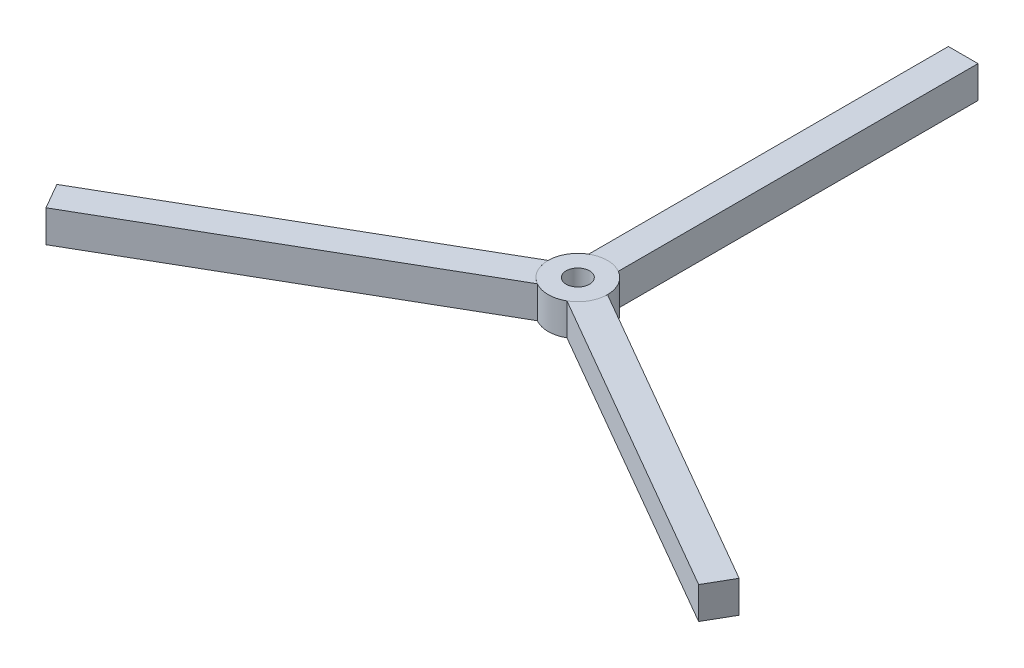
SolidWorks part; units mm, degrees
ref_plane "Front Plane" through (0, 0, 0) normal (0, 0, 1) x (1, 0, 0)
ref_plane "Top Plane" through (0, 0, 0) normal (0, 1, 0) x (1, 0, 0)
ref_plane "Right Plane" through (0, 0, 0) normal (1, 0, 0) x (0, 0, -1)
sketch "Sketch1" plane through (0, 0, 0) normal (0, 1, 0) x (1, 0, 0)
  circle A0 centre (0, 0) radius 6.35
  circle A1 centre (0, 0) radius 2.5
  dimension "D1" = 12.7
  dimension "D2" = 5
extrude "Boss-Extrude1" add sketch "Sketch1" along normal blind 6.858
ref_plane "Plane1" through (0, 0, -6.35) normal (0, 0, -1) x (-1, 0, 0)
sketch "Sketch3" plane through (0, 0, -6.35) normal (0, 0, -1) x (-1, 0, 0)
  line L0 (6.35, 6.858) -> (-6.35, 6.858) construction
  line L1 (-3.175, 6.858) -> (3.175, 6.858)
  line L2 (-3.175, 6.858) -> (-3.175, 0)
  line L3 (-3.175, 0) -> (3.175, 0)
  line L4 (3.175, 6.858) -> (3.175, 0)
  line L5 (-6.35, 0) -> (6.35, 0) construction
  dimension "D1" = 6.35
  dimension "D2" = 3.175
extrude "Boss-Extrude2" add sketch "Sketch3" along normal blind 76.2 and the other way up to surface separate body other way up to face at (0, 6.858, 6.35)
pattern_circular "CirPattern5" count 3 over 360 about axis through (0, 0, 0) along (0, 1, 0) of bodies 102
